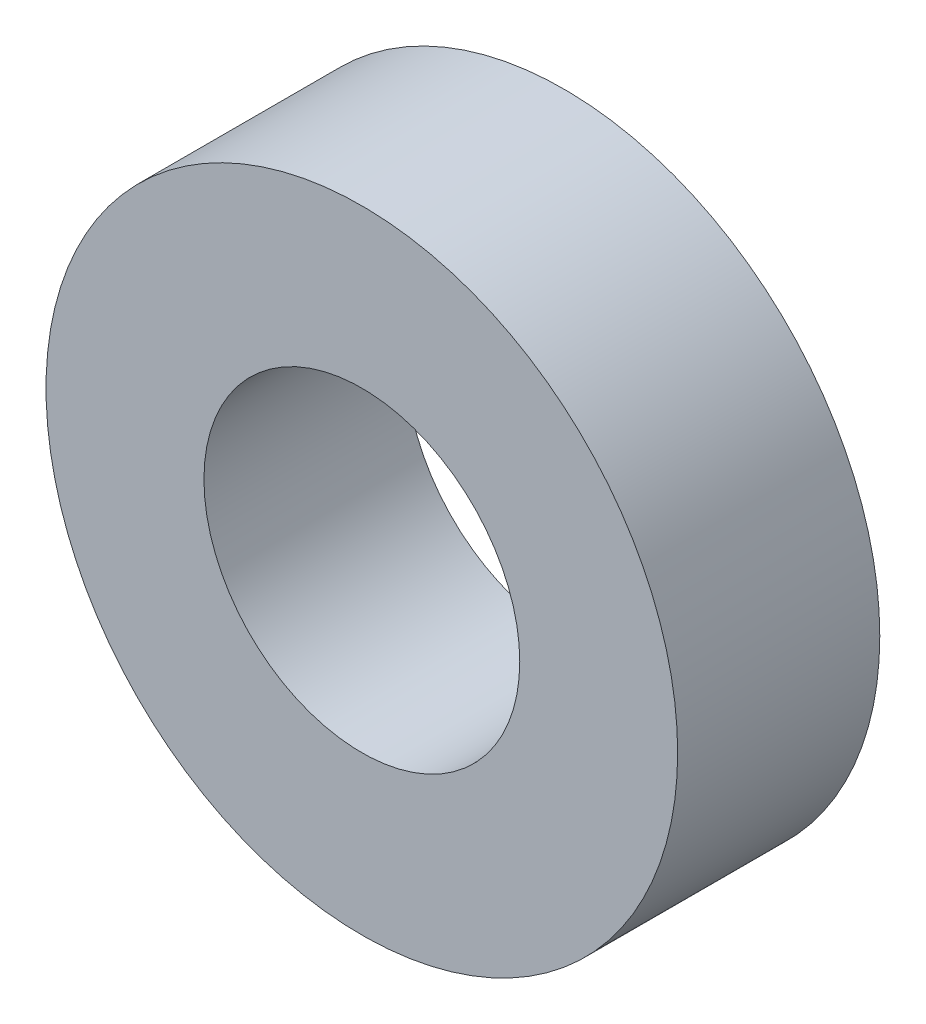
SolidWorks part; units mm, degrees
material "Nitrile Rubber"
ref_plane "Front Plane" through (0, 0, 0) normal (0, 0, 1) x (1, 0, 0)
ref_plane "Top Plane" through (0, 0, 0) normal (0, 1, 0) x (1, 0, 0)
ref_plane "Right Plane" through (0, 0, 0) normal (1, 0, 0) x (0, 0, -1)
sketch "Sketch1" plane through (0, 0, 0) normal (0, 0, 1) x (1, 0, 0)
  circle A0 centre (0, 0) radius 25
  circle A1 centre (0, 0) radius 12.5
  dimension "D1" = 50
  dimension "D2" = 25
extrude "Extrude1" add sketch "Sketch1" along normal blind 16
